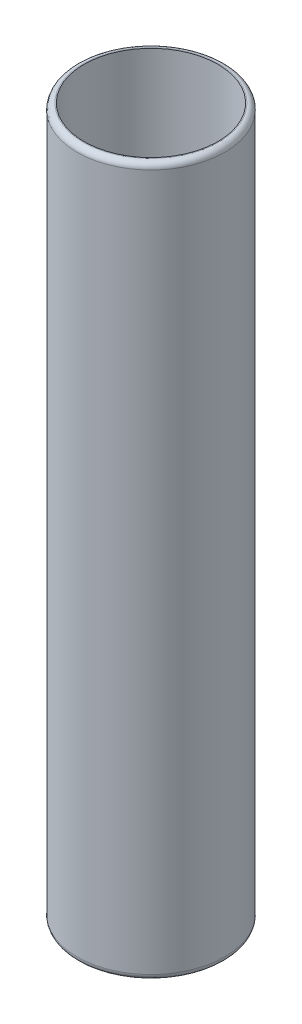
SolidWorks part; units mm, degrees
ref_plane "Front Plane" through (0, 0, 0) normal (0, 0, 1) x (1, 0, 0)
ref_plane "Top Plane" through (0, 0, 0) normal (0, 1, 0) x (1, 0, 0)
ref_plane "Right Plane" through (0, 0, 0) normal (1, 0, 0) x (0, 0, -1)
sketch "Sketch1" plane through (0, 0, 0) normal (0, 1, 0) x (1, 0, 0)
  circle A0 centre (0, 0) radius 15.875
  circle A1 centre (0, 0) radius 14.4018
  dimension "D1" = 31.75
  dimension "D2" = 1.4732
extrude "Boss-Extrude1" add sketch "Sketch1" along normal blind 152.4
fillet "Fillet1" radius 1.27 2 edges at (0, 0, 15.875) (0, 152.4, 15.875)
